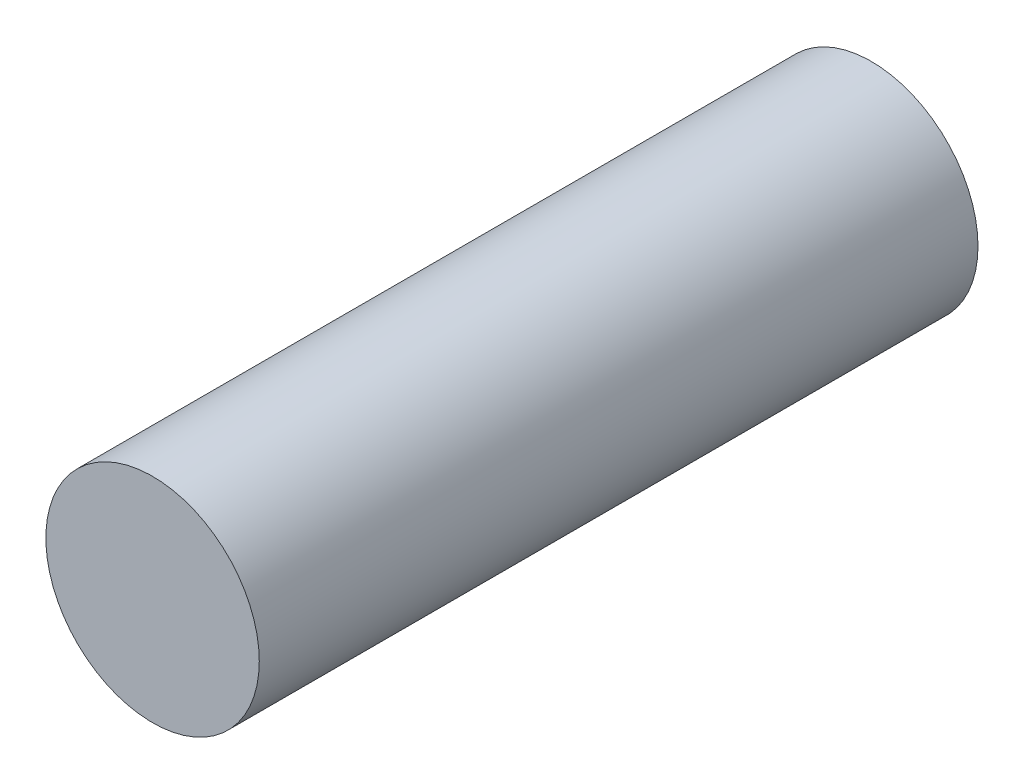
SolidWorks part; units mm, degrees
ref_plane "Front Plane" through (0, 0, 0) normal (0, 0, 1) x (1, 0, 0)
ref_plane "Top Plane" through (0, 0, 0) normal (0, 1, 0) x (1, 0, 0)
ref_plane "Right Plane" through (0, 0, 0) normal (1, 0, 0) x (0, 0, -1)
sketch "Sketch3" plane through (0, 0, 0) normal (0, 0, 1) x (1, 0, 0)
  circle A0 centre (-14.9653, 8.7751) radius 12.446
  dimension "D1" = 24.892
extrude "Boss-Extrude1" add sketch "Sketch3" along normal blind 83.82
